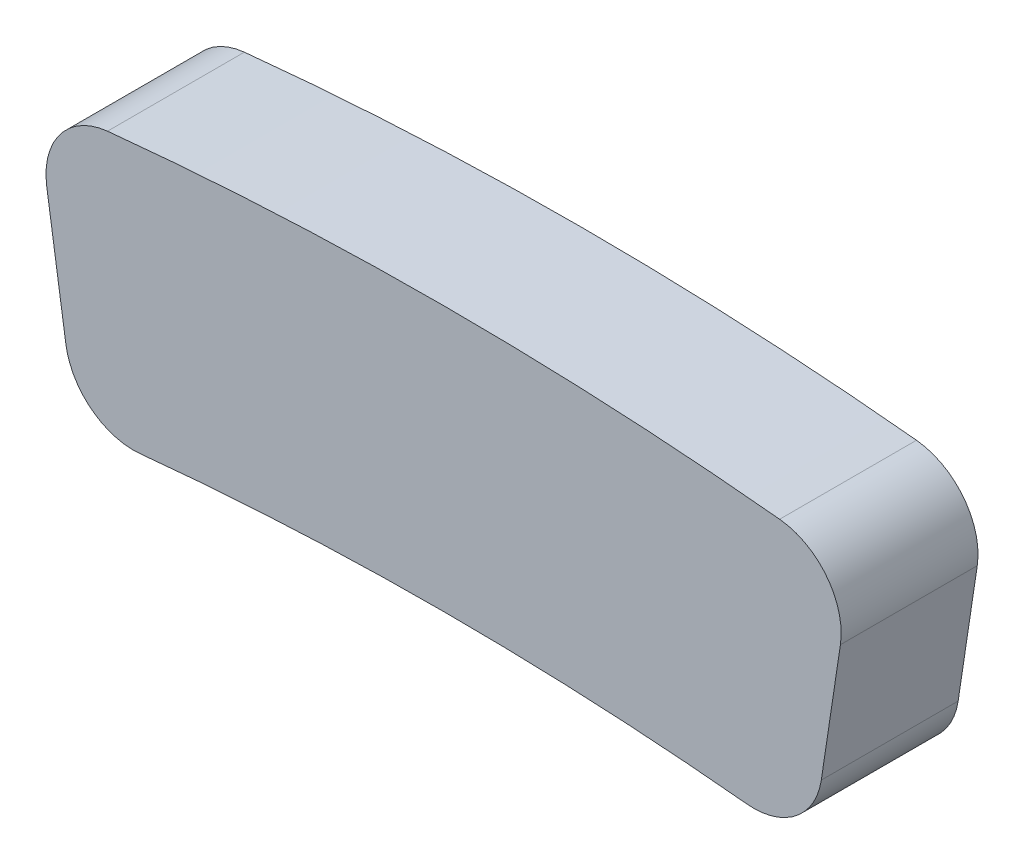
SolidWorks part; units mm, degrees
material "ABS"
ref_plane "Front Plane" through (0, 0, 0) normal (0, 0, 1) x (1, 0, 0)
ref_plane "Top Plane" through (0, 0, 0) normal (0, 1, 0) x (1, 0, 0)
ref_plane "Right Plane" through (0, 0, 0) normal (1, 0, 0) x (0, 0, -1)
sketch "Sketch1" plane through (0, 0, 0) normal (0, 0, 1) x (1, 0, 0)
  line L0 (-14.9042, 98.8831) -> (-12.9667, 86.0283) construction
  line L1 (12.9667, 86.0283) -> (14.9042, 98.8831) construction
  line L2 (0, 100) -> (0, 0) construction
  line L3 (-11.9086, 96.641) -> (-10.754, 88.9805)
  line L4 (10.754, 88.9805) -> (11.9086, 96.641)
  circle A0 centre (0, 0) radius 87 construction
  circle A1 centre (0, 0) radius 100 construction
  circle A2 centre (0, 0) radius 87 construction
  circle A3 centre (0, 0) radius 100 construction
  circle A4 centre (0, 0) radius 100 construction
  arc A5 (14.9042, 98.8831) -> (-14.9042, 98.8831) centre (0, 0) ccw construction
  arc A6 (12.9667, 86.0283) -> (-12.9667, 86.0283) centre (0, 0) ccw construction
  arc A7 (10.754, 88.9805) -> (-10.754, 88.9805) centre (0, 0) ccw
  arc A8 (11.9086, 96.641) -> (-11.9086, 96.641) centre (0, 0) ccw
  dimension "D1" = 17.143
  dimension "D2" = 2.628
extrude "Boss-Extrude1" add sketch "Sketch1" along normal up to vertex (4 mm away)
fillet "Fillet1" radius 2 4 edges at (11.9086, 96.641, 2) (10.754, 88.9805, 2) (-10.754, 88.9805, 2) (-11.9086, 96.641, 2)
equation "\"D1@Sketch1\"=360 / 21"
